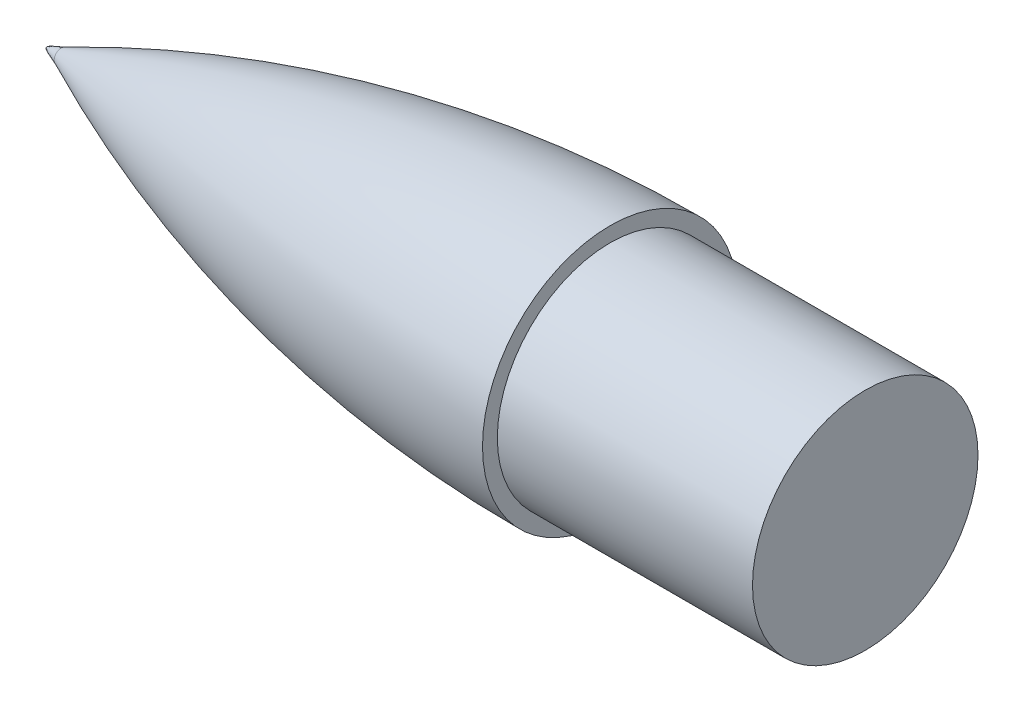
SolidWorks part; units mm, degrees
ref_plane "Front Plane" through (0, 0, 0) normal (0, 0, 1) x (1, 0, 0)
ref_plane "Top Plane" through (0, 0, 0) normal (0, 1, 0) x (1, 0, 0)
ref_plane "Right Plane" through (0, 0, 0) normal (1, 0, 0) x (0, 0, -1)
sketch "Sketch2" plane through (0, 0, 0) normal (0, 0, 1) x (1, 0, 0)
  line L0 (0, 441.2674) -> (0, 436.2674) construction
  line L1 (0, 441.2674) -> (0, 436.2674)
  line L2 (-178.0795, 398.2674) -> (-190, 398.2674)
  line L3 (0, 436.2674) -> (86, 436.2674)
  line L4 (86, 436.2674) -> (86, 398.2674)
  line L6 (86, 398.2674) -> (81, 398.2674)
  line L7 (-5, 436.2388) -> (-5, 431.2674)
  line L8 (-5, 431.2674) -> (81, 431.2674)
  line L12 (0, 403.2674) -> (-166.4471, 403.2674) construction
  line L13 (0, 398.2674) -> (-190, 398.2674) construction
  line L16 (81, 403.2674) -> (0, 403.2674) construction
  line L17 (86, 398.2674) -> (0, 398.2674) construction
  line L18 (81, 398.2674) -> (81, 431.2674)
  line L19 (81, 431.2674) -> (81, 403.2674) construction
  line L20 (-190, 398.2674) -> (-231.9218, 398.2674) construction
  arc A0 (0, 441.2674) -> (-190, 398.2674) centre (0, 0) ccw
  arc A3 (-5, 436.2388) -> (-166.4471, 403.2674) centre (0, 0) ccw construction
  arc A5 (-5, 436.2388) -> (-178.0795, 398.2674) centre (0, 0) ccw
  dimension "D3" = 86
  dimension "D4" = 5
  dimension "D5" = 5
revolve "Revolve1" add sketch "Sketch2" angle 360 about L20
sketch "Sketch3" plane through (0, 0, 0) normal (0, 0, 1) x (1, 0, 0)
  line L0 (-190, 398.2674) -> (-185, 398.2674)
  line L1 (-185, 398.2674) -> (-185, 400.6145)
  arc A0 (0, 441.2674) -> (-190, 398.2674) centre (0, 0) ccw construction
  arc A1 (-185, 400.6145) -> (-190, 398.2674) centre (0, 0) ccw
  dimension "D1" = 5
revolve "Cut-Revolve1" cut sketch "Sketch3" angle 360 about L0
sketch "Sketch4" plane through (0, 0, 0) normal (0, 0, 1) x (1, 0, 0)
  line L0 (-185, 398.2674) -> (-190, 398.2674)
  line L1 (-185, 400.6145) -> (-185, 395.9204) construction
  line L2 (-185, 398.2674) -> (-185, 400.6145)
  spline S0 degree 3 poles (-185, 400.6145) (-188.2043, 399.408) (-189.9355, 398.8377) (-190, 398.2674) knots 0 0 0 0 0.5 0.5 0.5 0.5
  dimension "D1" = 5
revolve "Revolve2" add sketch "Sketch4" angle 360 about L0
